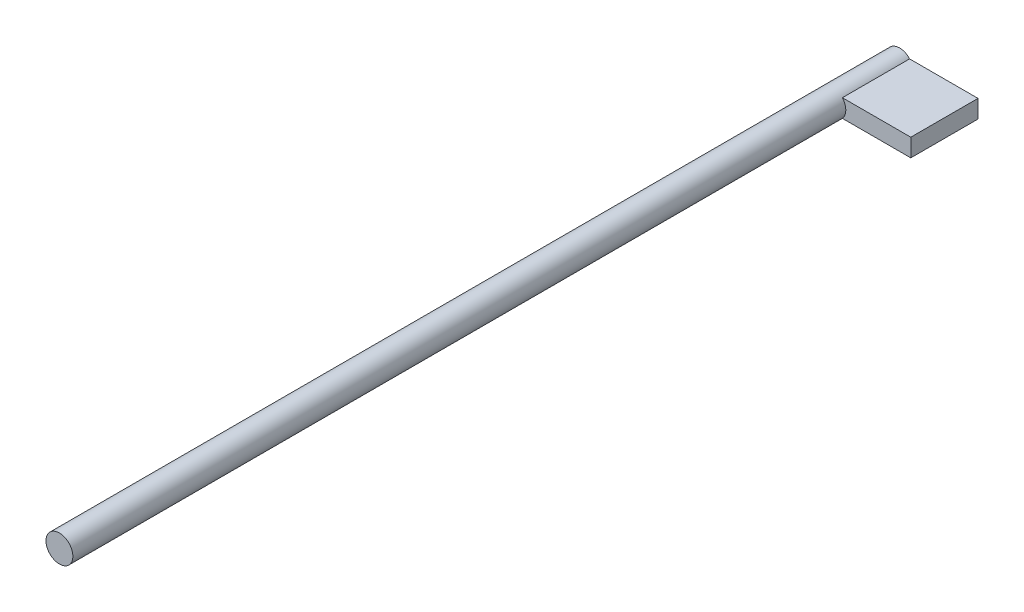
SolidWorks part; units mm, degrees
ref_plane "Front Plane" through (0, 0, 0) normal (0, 0, 1) x (1, 0, 0)
ref_plane "Top Plane" through (0, 0, 0) normal (0, 1, 0) x (1, 0, 0)
ref_plane "Right Plane" through (0, 0, 0) normal (1, 0, 0) x (0, 0, -1)
sketch "Sketch1" plane through (0, 0, 0) normal (0, 0, 1) x (1, 0, 0)
  circle A0 centre (0, 0) radius 6
  dimension "D1" = 12
extrude "Boss-Extrude1" add sketch "Sketch1" against normal blind 375
ref_plane "Plane1" through (0, 0, 0) normal (1, 0, 0) x (0, 0, -1)
sketch "Sketch2" plane through (0, 0, 0) normal (1, 0, 0) x (0, 0, -1)
  line L0 (375, 0) -> (345, 0) construction
  line L1 (375, -6) -> (375, 6) construction
  line L3 (345, -4) -> (375, -4)
  line L4 (345, -4) -> (345, 4)
  line L5 (345, 4) -> (375, 4)
  line L6 (375, -4) -> (375, 4)
  line L7 (345, -4) -> (375, 4) construction
  line L8 (345, 4) -> (375, -4) construction
  point P5 (360, 0)
  dimension "D1" = 30
  dimension "D2" = 8
extrude "Boss-Extrude2" add sketch "Sketch2" along normal blind 35 contours L5 L6 L3 L4
